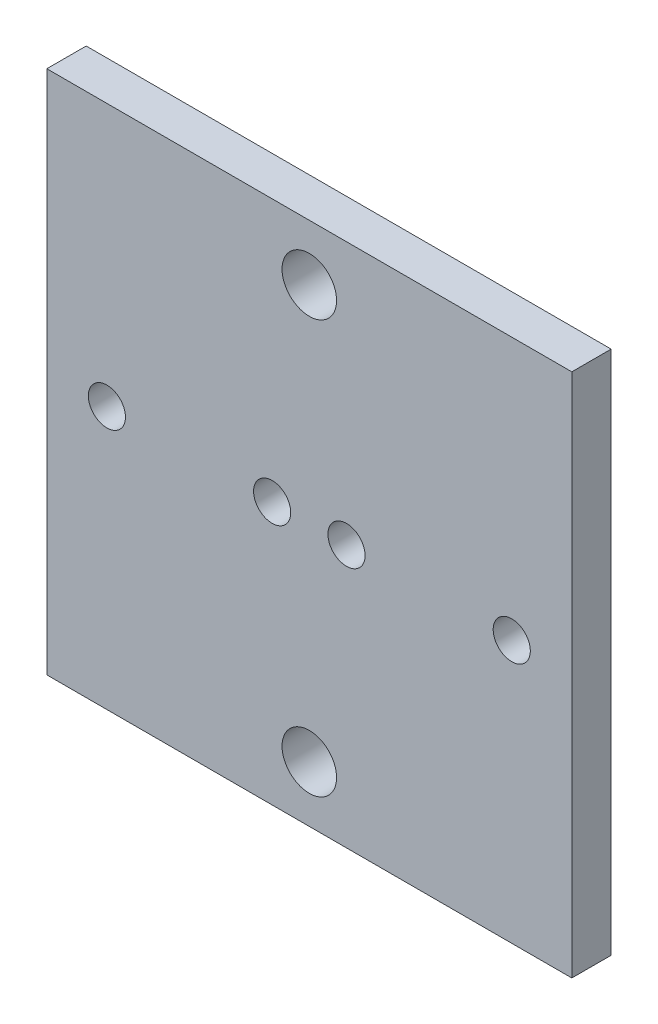
SolidWorks part; units mm, degrees
ref_plane "Front Plane" through (0, 0, 0) normal (0, 0, 1) x (1, 0, 0)
ref_plane "Top Plane" through (0, 0, 0) normal (0, 1, 0) x (1, 0, 0)
ref_plane "Right Plane" through (0, 0, 0) normal (1, 0, 0) x (0, 0, -1)
sketch "Sketch1" plane through (0, 0, 0) normal (0, 0, 1) x (1, 0, 0)
  line L0 (0, 30.5) -> (0, -30.5)
  line L1 (-5.08, 30.5) -> (5.08, 30.5)
  line L2 (-5.08, 30.5) -> (-5.08, -30.5)
  line L3 (-5.08, -30.5) -> (5.08, -30.5)
  line L4 (5.08, 30.5) -> (5.08, -30.5)
  line L5 (-30.5, 0) -> (30.5, 0)
  line L6 (-30.5, 5.08) -> (30.5, 5.08)
  line L7 (-30.5, 5.08) -> (-30.5, -5.08)
  line L8 (-30.5, -5.08) -> (30.5, -5.08)
  line L9 (30.5, 5.08) -> (30.5, -5.08)
  line L10 (5.08, -30.5) -> (30.5, -30.5)
  line L11 (30.5, -30.5) -> (30.5, -5.08)
  line L12 (30.5, 5.08) -> (30.5, 30.5)
  line L13 (30.5, 30.5) -> (-30.5, 30.5)
  line L14 (-30.5, 30.5) -> (-30.5, -30.5)
  line L15 (-30.5, -30.5) -> (-5.08, -30.5)
  circle A0 centre (0, 25) radius 3.3
  circle A1 centre (0, -25) radius 3.3
  circle A2 centre (-24.5, 0) radius 2.2479
  circle A3 centre (24.5, 0) radius 2.2479
  circle A4 centre (-4.5, 0) radius 2.2479
  circle A5 centre (4.5, 0) radius 2.2479
  dimension "D5" = 50
  dimension "D11" = 49
  dimension "D13" = 20
  dimension "D14" = 20
  dimension "D1" = 61
  dimension "D2" = 30.5
  dimension "D3" = 10.16
  dimension "D4" = 5.08
  dimension "D6" = 25
  dimension "D7" = 61
  dimension "D8" = 30.5
  dimension "D9" = 10.16
  dimension "D10" = 5.08
  dimension "D12" = 24.5
extrude "Boss-Extrude5" add sketch "Sketch1" along normal blind 4.7625 contours A0 L0 L1 L2 L6 | A0 L0 L6 L4 L1 | A5 L5 A3 L9 L6 L4 | A5 L4 L8 L9 L5 A3 | A5 L5 L0 L8 L4 | A4 L2 L8 L0 L5 | A5 L4 L6 L0 L5 | A4 L5 L0 L6 L2 | A4 L2 L6 L7 L5 A2 | A4 L5 A2 L7 L8 L2 | A1 L0 L8 L2 L3 | A1 L0 L3 L4 L8 | L13 L14 L6 L2 | L12 L13 L4 L6 | L10 L11 L8 L4 | L14 L15 L2 L8
sketch "Sketch3" plane through (-30.5, 0, 0) normal (-1, 0, 0) x (0, 0, 1)
  line L1 (0, -30.5) -> (4.7625, -30.5)
  line L2 (0, -30.5) -> (0, 30.5)
  line L3 (0, 30.5) -> (4.7625, 30.5)
  line L4 (4.7625, -30.5) -> (4.7625, 30.5)
extrude "Boss-Extrude6" add sketch "Sketch3" along normal blind 1.27
sketch "Sketch4" plane through (30.5, 0, 0) normal (1, 0, 0) x (0, 0, -1)
  line L1 (-4.7625, -30.5) -> (0, -30.5)
  line L2 (-4.7625, -30.5) -> (-4.7625, 30.5)
  line L3 (-4.7625, 30.5) -> (0, 30.5)
  line L4 (0, -30.5) -> (0, 30.5)
extrude "Boss-Extrude9" add sketch "Sketch4" along normal blind 1.27
sketch "Sketch6" plane through (0, -30.5, 0) normal (0, -1, 0) x (1, 0, 0)
  line L1 (-31.77, 0) -> (31.77, 0)
  line L2 (-31.77, 0) -> (-31.77, 4.7625)
  line L3 (-31.77, 4.7625) -> (31.77, 4.7625)
  line L4 (31.77, 0) -> (31.77, 4.7625)
extrude "Boss-Extrude10" add sketch "Sketch6" along normal blind 1.27
sketch "Sketch7" plane through (0, 30.5, 0) normal (0, 1, 0) x (1, 0, 0)
  line L1 (-31.77, -4.7625) -> (31.77, -4.7625)
  line L2 (-31.77, -4.7625) -> (-31.77, 0)
  line L3 (-31.77, 0) -> (31.77, 0)
  line L4 (31.77, -4.7625) -> (31.77, 0)
extrude "Boss-Extrude11" add sketch "Sketch7" along normal blind 1.27
